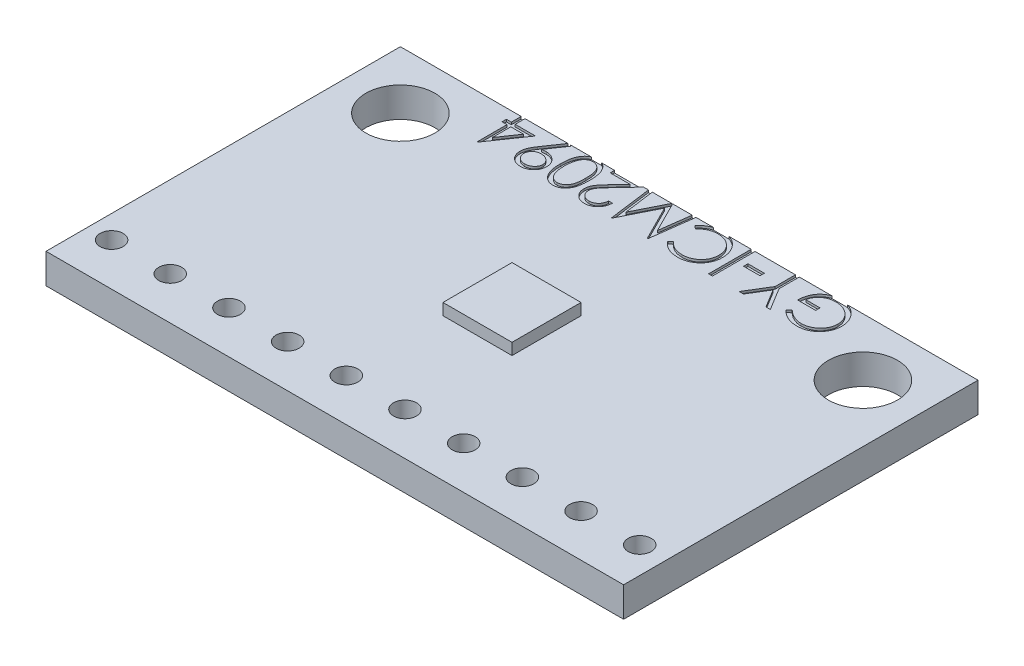
SolidWorks part; units mm, degrees
ref_plane "Front Plane" through (0, 0, 0) normal (0, 0, 1) x (1, 0, 0)
ref_plane "Top Plane" through (0, 0, 0) normal (0, 1, 0) x (1, 0, 0)
ref_plane "Right Plane" through (0, 0, 0) normal (1, 0, 0) x (0, 0, -1)
sketch "Sketch2" plane through (0, 0, 0) normal (0, 1, 0) x (1, 0, 0)
  line L0 (-10.05, 6.7) -> (-7.5954, 6.7) construction
  line L1 (-12.55, 7.7) -> (12.55, 7.7)
  line L2 (-12.55, 7.7) -> (-12.55, -7.7)
  line L3 (-12.55, -7.7) -> (12.55, -7.7)
  line L4 (12.55, 7.7) -> (12.55, -7.7)
  line L5 (-12.55, 7.7) -> (12.55, -7.7) construction
  line L6 (-12.55, -7.7) -> (12.55, 7.7) construction
  line L7 (-11.55, 5.2) -> (-11.55, 3.5457) construction
  line L8 (11.55, 5.2) -> (11.55, 4.3807) construction
  line L9 (0, 0) -> (0, -7.7) construction
  circle A0 centre (-10.05, 5.2) radius 1.5
  circle A1 centre (10.05, 5.2) radius 1.5
  circle A2 centre (-11.55, -5.8506) radius 0.5
  circle A3 centre (-9, -5.8506) radius 0.5
  circle A4 centre (-6.45, -5.8506) radius 0.5
  circle A5 centre (-3.9, -5.8506) radius 0.5
  circle A6 centre (-1.35, -5.8506) radius 0.5
  circle A7 centre (1.2, -5.8506) radius 0.5
  circle A8 centre (3.75, -5.8506) radius 0.5
  circle A9 centre (6.3, -5.8506) radius 0.5
  circle A10 centre (8.85, -5.8506) radius 0.5
  circle A11 centre (11.4, -5.8506) radius 0.5
  point P0 (0, 0)
  dimension "D3" = 1
  dimension "D6" = 3
  dimension "D7" = 3
  dimension "D8" = 1
  dimension "D9" = 1
  dimension "D1" = 25.1
  dimension "D2" = 15.4
  dimension "D4" = 1
  dimension "D5" = 1
  dimension "D10" = 10
extrude "Boss-Extrude1" add sketch "Sketch2" along normal blind 1.3
sketch "Sketch3" plane through (0, 1.3, 0) normal (0, 1, 0) x (1, 0, 0)
  line L1 (-1.5, 1.5) -> (1.5, 1.5)
  line L2 (-1.5, 1.5) -> (-1.5, -1.5)
  line L3 (-1.5, -1.5) -> (1.5, -1.5)
  line L4 (1.5, 1.5) -> (1.5, -1.5)
  line L5 (-1.5, 1.5) -> (1.5, -1.5) construction
  line L6 (-1.5, -1.5) -> (1.5, 1.5) construction
  point P0 (0, 0)
  dimension "D1" = 3
  dimension "D2" = 3
extrude "Boss-Extrude2" add sketch "Sketch3" along normal blind 0.5
sketch "Sketch4" plane through (0, 1.3, 0) normal (0, 1, 0) x (1, 0, 0)
  text T0 "GY-ICM2094" font "Century Gothic" height in points 7
  point P1 (0, 0)
  point P4 (0, 0)
  point P5 (0, 0)
extrude "Cut-Extrude1" cut sketch "Sketch4" against normal blind 0.1
